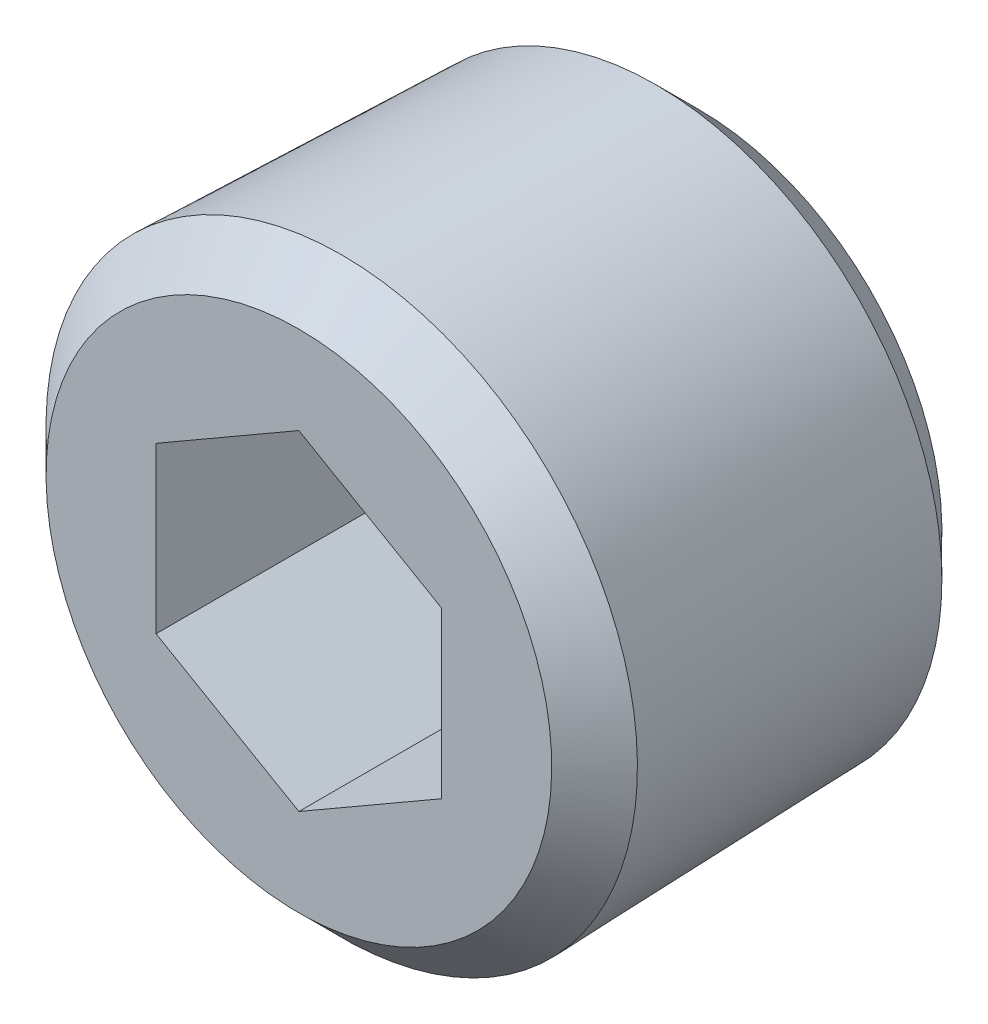
SolidWorks part; units mm, degrees
material "4140 H/T"
ref_plane "Front Plane" through (0, 0, 0) normal (0, 0, 1) x (1, 0, 0)
ref_plane "Top Plane" through (0, 0, 0) normal (0, 1, 0) x (1, 0, 0)
ref_plane "Right Plane" through (0, 0, 0) normal (1, 0, 0) x (0, 0, -1)
sketch "Sketch1" plane through (0, 0, 0) normal (1, 0, 0) x (0, 0, -1)
  line L0 (0, 0) -> (0, 8.5066)
  line L1 (0, 8.5066) -> (-1.5, 10.0066)
  line L2 (-1.5, 10.0066) -> (-12.5, 10.35)
  line L3 (-12.5, 10.35) -> (-14, 8.85)
  line L4 (-14, 8.85) -> (-14, 0)
  line L5 (0, 0) -> (-14, 0) construction
  line L6 (0, 0) -> (-14, 0)
  dimension "D1" = 14
  dimension "D2" = 20.7
  dimension "D3" = 1.788
  dimension "D4" = 1.5
  dimension "D5" = 45
  dimension "D6" = 1.5
  dimension "D7" = 45
revolve "Revolve1" add sketch "Sketch1" angle 360 about L5
cosmetic thread "Cosmetic Thread1" parameters "D2"=17.1132
sketch "Sketch2" plane through (0, 0, 14) normal (0, 0, 1) x (1, 0, 0)
  line L1 (0, -5.7735) -> (5, -2.8868)
  line L2 (5, -2.8868) -> (5, 2.8868)
  line L3 (5, 2.8868) -> (0, 5.7735)
  line L4 (0, 5.7735) -> (-5, 2.8868)
  line L5 (-5, 2.8868) -> (-5, -2.8868)
  line L6 (-5, -2.8868) -> (0, -5.7735)
  circle A0 centre (0, 0) radius 5 construction
extrude "Cut-Extrude1" cut sketch "Sketch2" against normal blind 10
